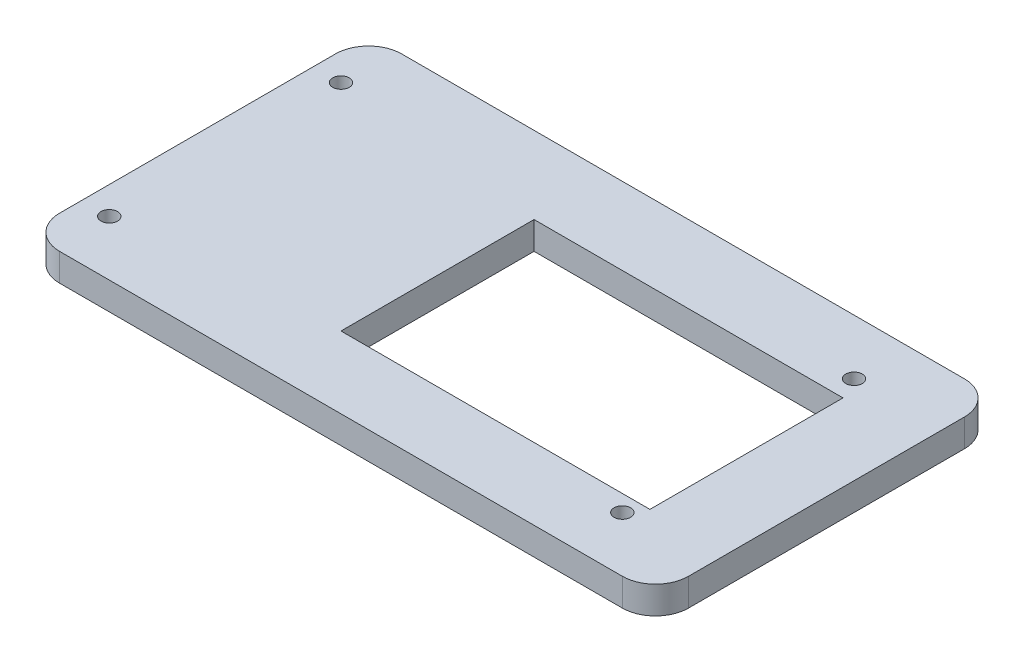
SolidWorks part; units mm, degrees
material "Плата обработки данных, простая"
ref_plane "Спереди" through (0, 0, 0) normal (0, 0, 1) x (1, 0, 0)
ref_plane "Сверху" through (0, 0, 0) normal (0, 1, 0) x (1, 0, 0)
ref_plane "Справа" through (0, 0, 0) normal (1, 0, 0) x (0, 0, -1)
sketch "Эскиз1" plane through (0, 0, 0) normal (0, 1, 0) x (1, 0, 0)
  line L0 (-31.5, -31) -> (-82.5, -31)
  line L2 (31.5, -31) -> (31.5, 31)
  line L3 (-82.5, 31) -> (31.5, 31)
  line L4 (-82.5, -31) -> (-82.5, 21)
  line L5 (31.5, -31) -> (-31.5, -31)
  line L7 (-38.5, -18) -> (17.5, -18)
  line L9 (-38.5, -18) -> (-38.5, 17)
  line L10 (-82.5, 31) -> (-82.5, 21)
  line L13 (-38.5, 17) -> (17.5, 17)
  line L15 (17.5, -18) -> (17.5, 17)
  point P0 (0, 0)
extrude "Бобышка-Вытянуть1" add sketch "Эскиз1" along normal blind 5
sketch "Эскиз3" plane through (0, 0, 0) normal (0, -1, 0) x (1, 0, 0)
  circle A0 centre (15.5, 21) radius 1.5
  circle A1 centre (15.5, -21) radius 1.5
  circle A2 centre (-77.5, 21) radius 1.5
  circle A3 centre (-77.5, -21) radius 1.5
extrude "Вырез-Вытянуть1" cut sketch "Эскиз3" against normal blind 10
fillet "Скругление1" radius 6 4 edges at (31.5, 2.5, 31) (31.5, 2.5, -31) (-82.5, 2.5, -31) (-82.5, 2.5, 31)
